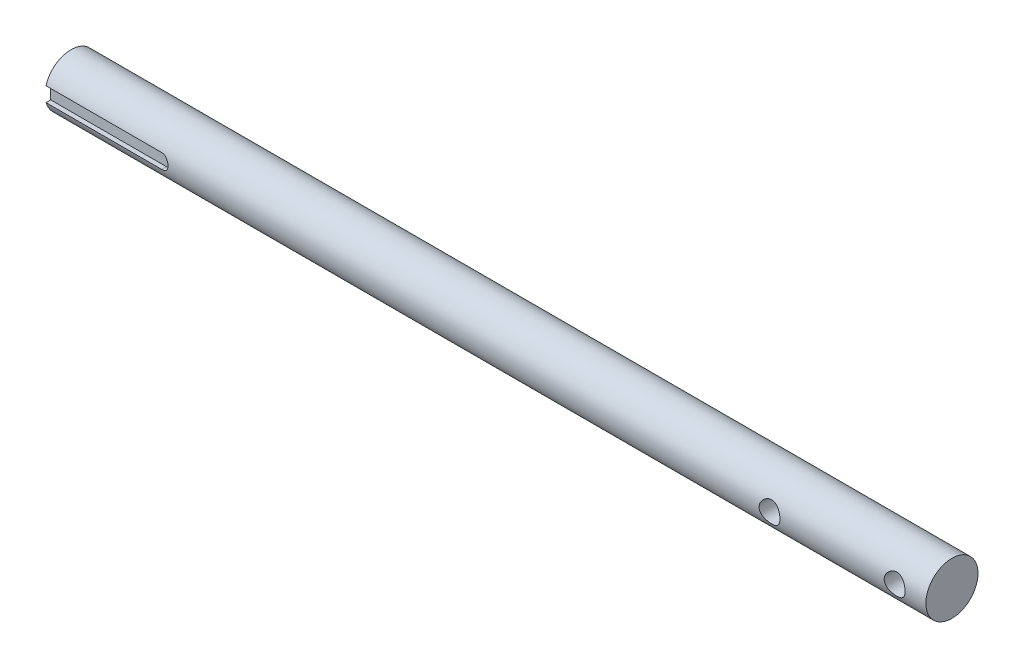
SolidWorks part; units mm, degrees
material "AISI 304"
ref_plane "Front Plane" through (0, 0, 0) normal (0, 0, 1) x (1, 0, 0)
ref_plane "Top Plane" through (0, 0, 0) normal (0, 1, 0) x (1, 0, 0)
ref_plane "Right Plane" through (0, 0, 0) normal (1, 0, 0) x (0, 0, -1)
sketch "Sketch1" plane through (0, 0, 0) normal (1, 0, 0) x (0, 0, -1)
  circle A0 centre (0, 0) radius 25
  dimension "D1" = 50
extrude "Boss-Extrude1" add sketch "Sketch1" along normal mid plane 845
sketch "Sketch2" plane through (0, 0, 0) normal (0, 0, 1) x (1, 0, 0)
  line L0 (422.5, -25) -> (422.5, 25) construction
  circle A0 centre (392.5, 0) radius 10
  circle A1 centre (272.5, 0) radius 10
  dimension "D1" = 20
  dimension "D2" = 20
  dimension "D3" = 30
  dimension "D4" = 150
extrude "Cut-Extrude1" cut sketch "Sketch2" against normal mid plane 320
ref_plane "Plane1" through (0, 0, 25) normal (0, 0, 1) x (1, 0, 0)
sketch "Sketch3" plane through (0, 0, 25) normal (0, 0, 1) x (1, 0, 0)
  line L0 (-402.5, 0) -> (-336.5, 0) construction
  line L1 (-402.5, 7) -> (-336.5, 7)
  line L2 (-402.5, -7) -> (-336.5, -7)
  line L3 (-422.5, 25) -> (-422.5, -25) construction
  arc A0 (-402.5, 7) -> (-402.5, -7) centre (-402.5, 0) ccw
  arc A1 (-336.5, -7) -> (-336.5, 7) centre (-336.5, 0) ccw
  point P3 (-369.5, 0)
  dimension "D1" = 14
  dimension "D2" = 66
  dimension "D3" = 20
extrude "Cut-Extrude2" [suppressed] cut sketch "Sketch3" against normal blind 5.5
sketch "Sketch4" plane through (0, 0, 25) normal (0, 0, 1) x (1, 0, 0)
  line L0 (-422.5, 0) -> (-311.5, 0) construction
  line L1 (-422.5, 7) -> (-311.5, 7)
  line L2 (-422.5, -7) -> (-311.5, -7)
  line L3 (-422.5, 25) -> (-422.5, -25) construction
  arc A0 (-422.5, 7) -> (-422.5, -7) centre (-422.5, 0) ccw
  arc A1 (-311.5, -7) -> (-311.5, 7) centre (-311.5, 0) ccw
  point P3 (-367, 0)
  dimension "D2" = 7
  dimension "D1" = 111
  dimension "D3" = 0
extrude "Cut-Extrude3" cut sketch "Sketch4" against normal blind 5.5
